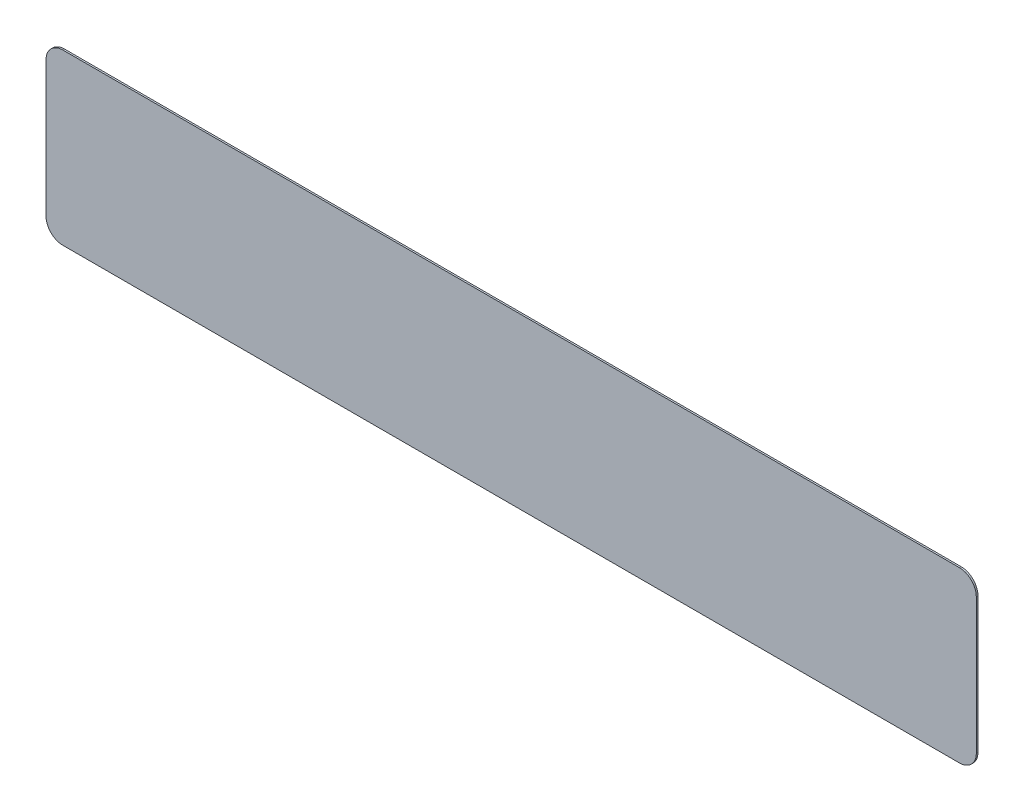
SolidWorks part; units mm, degrees
ref_plane "Спереди" through (0, 0, 0) normal (0, 0, 1) x (1, 0, 0)
ref_plane "Сверху" through (0, 0, 0) normal (0, 1, 0) x (1, 0, 0)
ref_plane "Справа" through (0, 0, 0) normal (1, 0, 0) x (0, 0, -1)
sketch "Эскиз1" plane through (0, 0, 0) normal (0, 0, 1) x (1, 0, 0)
  line L1 (-53, -10) -> (53, -10)
  line L2 (-55, -8) -> (-55, 8)
  line L3 (-53, 10) -> (53, 10)
  line L4 (55, -8) -> (55, 8)
  line L5 (-55, -10) -> (55, 10) construction
  line L6 (-55, 10) -> (55, -10) construction
  arc A0 (53, -10) -> (55, -8) centre (53, -8) ccw
  arc A1 (53, 10) -> (55, 8) centre (53, 8) cw
  arc A2 (-53, -10) -> (-55, -8) centre (-53, -8) cw
  arc A3 (-55, 8) -> (-53, 10) centre (-53, 8) cw
  point P0 (0, 0)
  dimension "D3" = 2
  dimension "D1" = 110
  dimension "D2" = 20
extrude "Бобышка-Вытянуть1" add sketch "Эскиз1" along normal blind 0.2
